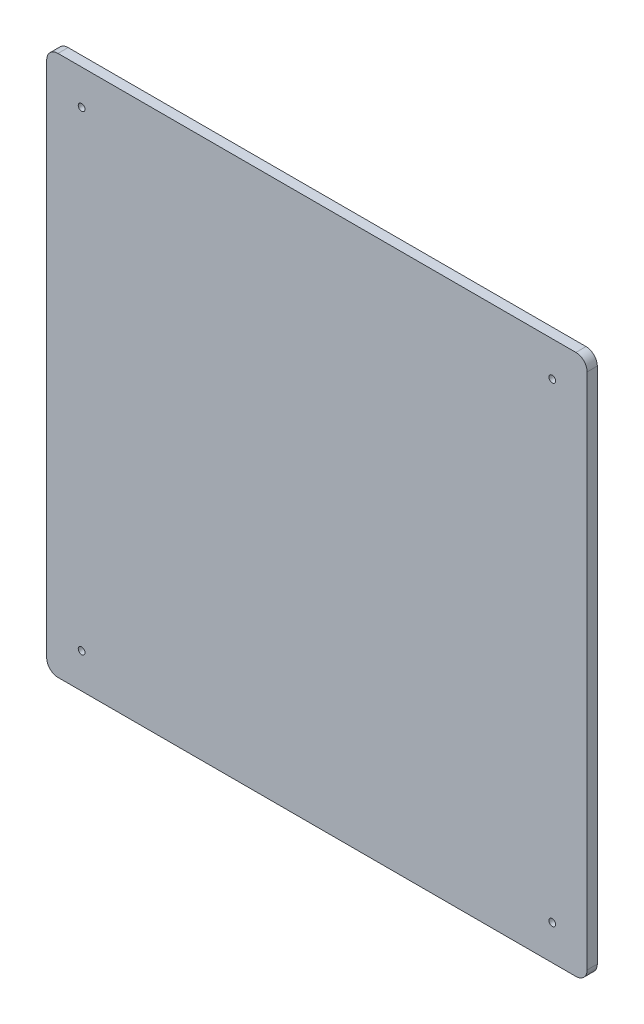
SolidWorks part; units mm, degrees
material "1023 Arkusz stali węglowej (SS)"
ref_plane "Płaszczyzna przednia" through (0, 0, 0) normal (0, 0, 1) x (1, 0, 0)
ref_plane "Płaszczyzna górna" through (0, 0, 0) normal (0, 1, 0) x (1, 0, 0)
ref_plane "Płaszczyzna prawa" through (0, 0, 0) normal (1, 0, 0) x (0, 0, -1)
sketch "Szkic1" plane through (0, 0, 0) normal (0, 0, 1) x (1, 0, 0)
  line L1 (-120, -120) -> (120, -120)
  line L2 (-120, -120) -> (-120, 120)
  line L3 (-120, 120) -> (120, 120)
  line L4 (120, -120) -> (120, 120)
  line L5 (0, 120) -> (0, -120) construction
  line L6 (-120, 0) -> (120, 0) construction
  point P0 (0, 0)
  dimension "D1" = 240
extrude "Dodanie-wyciągnięcie1" add sketch "Szkic1" along normal blind 4.5
sketch "Szkic2" plane through (0, 0, 0) normal (0, 0, -1) x (-1, 0, 0)
  line L1 (-104.5, -104.5) -> (104.5, -104.5) construction
  line L2 (-104.5, -104.5) -> (-104.5, 104.5) construction
  line L3 (-104.5, 104.5) -> (104.5, 104.5) construction
  line L4 (104.5, -104.5) -> (104.5, 104.5) construction
  line L5 (0, 104.5) -> (0, -104.5) construction
  line L6 (-104.5, 0) -> (104.5, 0) construction
  circle A0 centre (-104.5, 104.5) radius 1.5
  circle A1 centre (104.5, 104.5) radius 1.5
  circle A2 centre (-104.5, -104.5) radius 1.5
  circle A3 centre (104.5, -104.5) radius 1.5
  point P0 (0, 0)
  dimension "D2" = 3
  dimension "D1" = 209
extrude "Wytnij-wyciągnięcie1" cut sketch "Szkic2" against normal up to next
fillet "Zaokrąglenie1" radius 5 4 edges at (120, -120, 2.25) (-120, -120, 2.25) (-120, 120, 2.25) (120, 120, 2.25)
